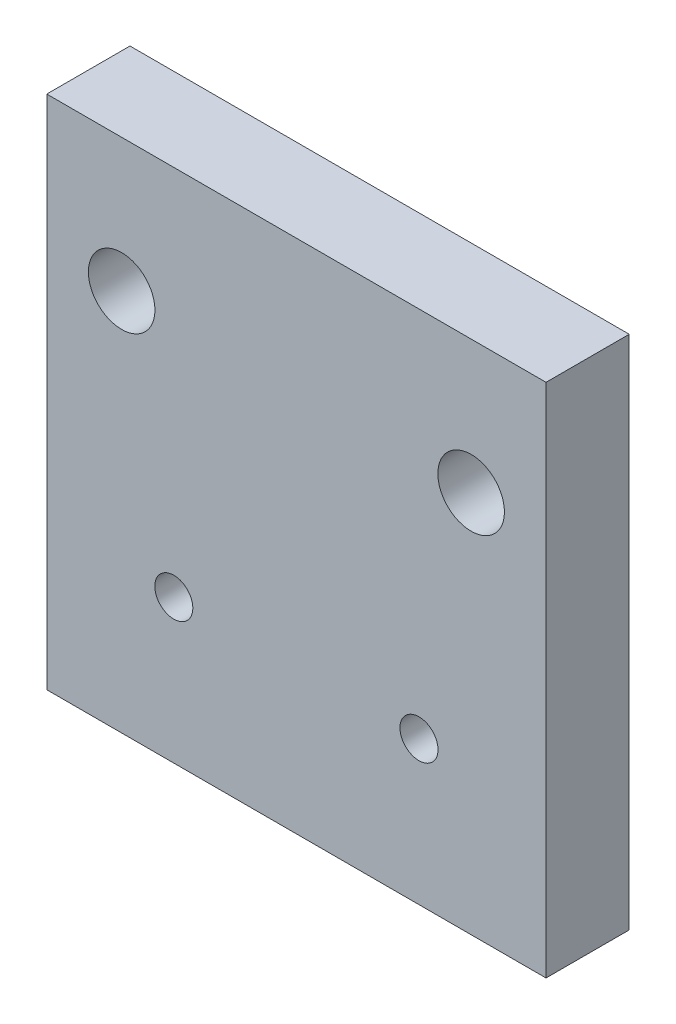
SolidWorks part; units mm, degrees
ref_plane "Front Plane" through (0, 0, 0) normal (0, 0, 1) x (1, 0, 0)
ref_plane "Top Plane" through (0, 0, 0) normal (0, 1, 0) x (1, 0, 0)
ref_plane "Right Plane" through (0, 0, 0) normal (1, 0, 0) x (0, 0, -1)
sketch "Sketch1" plane through (0, 0, 0) normal (0, 0, 1) x (1, 0, 0)
  line L1 (-15, 15.5) -> (15, 15.5)
  line L2 (-15, 15.5) -> (-15, -15.5)
  line L3 (-15, -15.5) -> (15, -15.5)
  line L4 (15, 15.5) -> (15, -15.5)
  dimension "D1" = 30
  dimension "D2" = 31
  dimension "D3" = 15.5
  dimension "D4" = 15
extrude "Boss-Extrude1" add sketch "Sketch1" along normal blind 5
sketch "Sketch2" plane through (0, 0, 5) normal (0, 0, 1) x (1, 0, 0)
  line L0 (-15, -15.5) -> (15, -15.5) construction
  line L1 (-15, 15.5) -> (-15, -15.5) construction
  line L2 (15, -15.5) -> (15, 15.5) construction
  line L3 (15, 15.5) -> (-15, 15.5) construction
  circle A1 centre (-7.366, -6.866) radius 1.143
  circle A3 centre (7.366, -6.866) radius 1.143
  circle A4 centre (-10.5, 7.5) radius 2
  circle A5 centre (10.5, 7.5) radius 2
  dimension "D1" = 2.286
  dimension "D2" = 2.286
  dimension "D6" = 7.634
  dimension "D7" = 4
  dimension "D8" = 4
  dimension "D3" = 8.634
  dimension "D4" = 8.634
  dimension "D5" = 7.634
  dimension "D9" = 8
  dimension "D10" = 4.5
  dimension "D11" = 4.5
extrude "Cut-Extrude1" cut sketch "Sketch2" against normal blind 10
